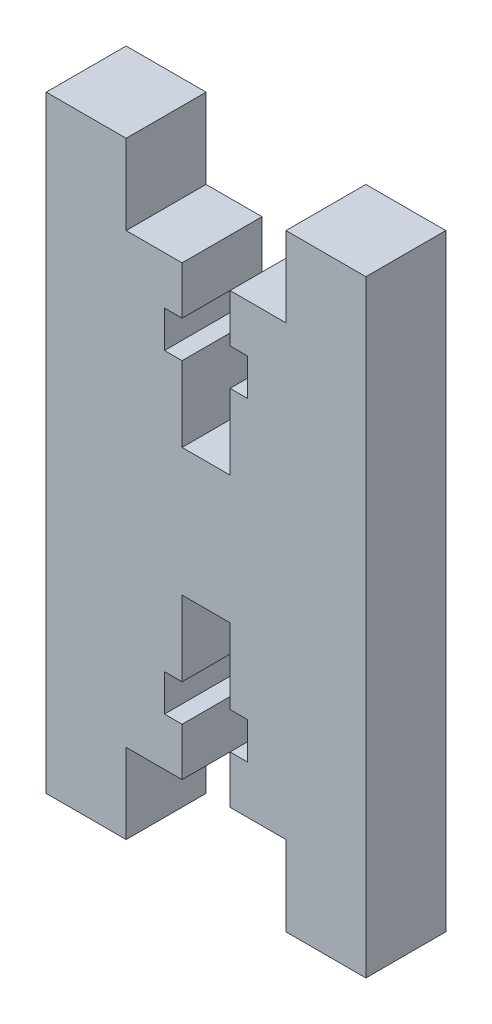
SolidWorks part; units mm, degrees
ref_plane "Plan de face" through (0, 0, 0) normal (0, 0, 1) x (1, 0, 0)
ref_plane "Plan de dessus" through (0, 0, 0) normal (0, 1, 0) x (1, 0, 0)
ref_plane "Plan de droite" through (0, 0, 0) normal (1, 0, 0) x (0, 0, -1)
sketch "Esquisse1" plane through (0, 0, 0) normal (0, 0, 1) x (1, 0, 0)
  line L0 (0, 0) -> (0, 31.5372) construction
  line L1 (0, 0) -> (21.493, 0) construction
  line L2 (-10, 14) -> (-10, -14)
  line L3 (10, 14) -> (10, -14)
  point P8 (10, 19)
  point P9 (10, -19)
  line B0 (-2.6, -11) -> (-2.6, -8.7)
  line B1 (1.5, -8.7) -> (1.5, -4)
  line B2 (-1.5, -4) -> (-1.5, -8.7)
  line B3 (-2.6, -8.7) -> (-1.5, -8.7)
  line B4 (0, -14) -> (0, -2.7792) construction
  line B5 (-1.5, -14) -> (-5, -14)
  line B6 (-5, -19) -> (-10, -19)
  line B7 (-10, -19) -> (-10, -14)
  line B8 (-5, -19) -> (-5, -14)
  line B9 (1.5, -14) -> (5, -14)
  line B10 (5, -14) -> (5, -19)
  line B11 (5, -19) -> (10, -19)
  line B12 (10, -19) -> (10, -14)
  line B13 (-1.5, -14) -> (1.5, -14) construction
  line B14 (1.5, -14) -> (1.5, -11)
  line B15 (1.5, -8.7) -> (2.6, -8.7)
  line B16 (2.6, -11) -> (1.5, -11)
  line B17 (1.5, -4) -> (-1.5, -4)
  line B18 (-1.5, -11) -> (-2.6, -11)
  line B19 (2.6, -8.7) -> (2.6, -11)
  line B20 (-1.5, -11) -> (-1.5, -14)
  line B21 (0, -4) -> (0, -14) construction
  line B22 (-2.6, 11) -> (-2.6, 8.7)
  line B23 (1.5, 8.7) -> (1.5, 4)
  line B24 (-1.5, 4) -> (-1.5, 8.7)
  line B25 (-2.6, 8.7) -> (-1.5, 8.7)
  line B26 (0, 14) -> (0, 2.7792) construction
  line B27 (-1.5, 14) -> (-5, 14)
  line B28 (-5, 19) -> (-10, 19)
  line B29 (-10, 19) -> (-10, 14)
  line B30 (-5, 19) -> (-5, 14)
  line B31 (1.5, 14) -> (5, 14)
  line B32 (5, 14) -> (5, 19)
  line B33 (5, 19) -> (10, 19)
  line B34 (10, 19) -> (10, 14)
  line B35 (-1.5, 14) -> (1.5, 14) construction
  line B36 (1.5, 14) -> (1.5, 11)
  line B37 (1.5, 8.7) -> (2.6, 8.7)
  line B38 (2.6, 11) -> (1.5, 11)
  line B39 (1.5, 4) -> (-1.5, 4)
  line B40 (-1.5, 11) -> (-2.6, 11)
  line B41 (2.6, 8.7) -> (2.6, 11)
  line B42 (-1.5, 11) -> (-1.5, 14)
  line B43 (0, 4) -> (0, 14) construction
  dimension "D1" = 14
sketch_block_instance "Insert M3 plots ep 5mm-1"
sketch_block "Insert M3 plots ep 5mm" parameters "D1"=10, "D2"=5, "D3"=5
sketch_block_instance "Decoupe Insert M3-4"
sketch_block "Decoupe Insert M3" parameters "D1"=5.2, "D2"=3, "D3"=2.3, "D4"=3, "D5"=10
sketch_block_instance "Insert M3 plots ep 5mm-3"
extrude "Boss.-Extru.1" add sketch "Esquisse1" along normal blind 5 contours B40 B42 B27 B30 B28 B29 L2 B7 B6 B8 B5 B20 B18 B0 B3 B2 B17 B1 B15 B19 B16 B14 B9 B10 B11 B12 L3 B34 B33 B32 B31 B36 B38 B41 B37 B23 B39 B24 B25 B22
